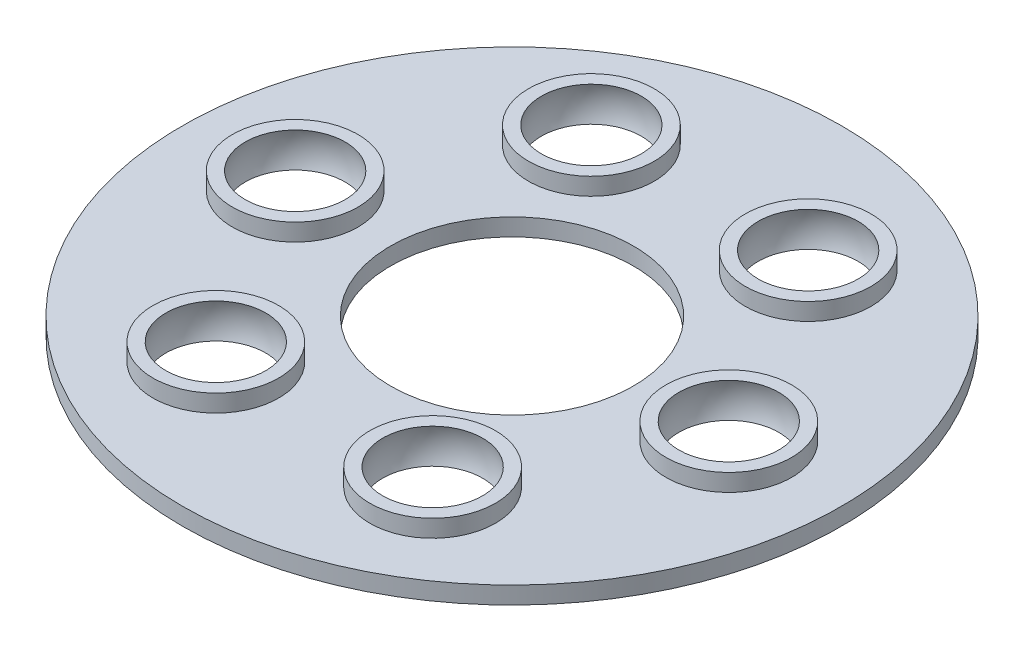
SolidWorks part; units mm, degrees
ref_plane "Front Plane" through (0, 0, 0) normal (0, 0, 1) x (1, 0, 0)
ref_plane "Top Plane" through (0, 0, 0) normal (0, 1, 0) x (1, 0, 0)
ref_plane "Right Plane" through (0, 0, 0) normal (1, 0, 0) x (0, 0, -1)
sketch "Sketch1" plane through (0, 0, 0) normal (0, 1, 0) x (1, 0, 0)
  circle A0 centre (0, 0) radius 19
  circle A1 centre (0, 0) radius 7
  circle A2 centre (-12.5, 0) radius 2.625
  circle A3 centre (-6.25, 10.8253) radius 2.625
  circle A4 centre (6.25, 10.8253) radius 2.625
  circle A5 centre (12.5, 0) radius 2.625
  circle A6 centre (6.25, -10.8253) radius 2.625
  circle A7 centre (-6.25, -10.8253) radius 2.625
  point P18 (0, 0)
  dimension "D1" = 5.25
  dimension "D3" = 14
  dimension "D4" = 38
  dimension "D2" = 12.5
  dimension "D5" = 6
extrude "Boss-Extrude1" add sketch "Sketch1" along normal blind 1
sketch "Sketch2" plane through (0, 1, 0) normal (0, 1, 0) x (1, 0, 0)
  circle A0 centre (-12.5, 0) radius 2.625 construction
  circle A1 centre (-12.5, 0) radius 2.625
extrude "Extrude-Thin1" add sketch "Sketch2" along normal blind 1 thin
sketch "Sketch3" plane through (0, 1, 0) normal (0, 1, 0) x (1, 0, 0)
  line L0 (-9.45, 0) -> (-15.55, 0)
  arc A1 (-9.45, 0) -> (-15.55, 0) centre (-12.5, 0) ccw
  circle A2 centre (-12.5, 0) radius 2.625 construction
  dimension "D1" = 6.1
revolve "Cut-Revolve1" cut sketch "Sketch3" angle 360 about L0
pattern_circular "CirPattern1" count 6 over 360 about axis through (0, 0, 0) along (0, 1, 0) of "Extrude-Thin1", "Cut-Revolve1"
